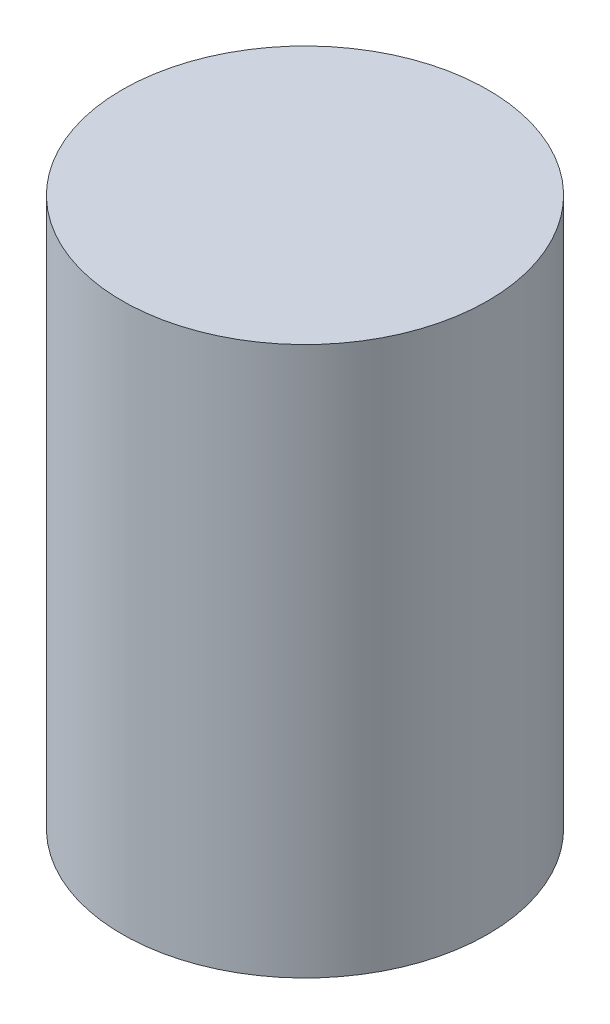
SolidWorks part; units mm, degrees
ref_plane "Front Plane" through (0, 0, 0) normal (0, 0, 1) x (1, 0, 0)
ref_plane "Top Plane" through (0, 0, 0) normal (0, 1, 0) x (1, 0, 0)
ref_plane "Right Plane" through (0, 0, 0) normal (1, 0, 0) x (0, 0, -1)
sketch "Sketch1" plane through (0, 0, 0) normal (0, 0, 1) x (1, 0, 0)
  line L1 (0, 750) -> (1000, 750)
  line L2 (0, 750) -> (0, -2250)
  line L3 (0, -2250) -> (1000, -2250)
  line L4 (1000, 750) -> (1000, -2250)
  dimension "D1" = 3000
  dimension "D2" = 1000
  dimension "D3" = 750
revolve "Revolve1" add sketch "Sketch1" angle 360 about L2
